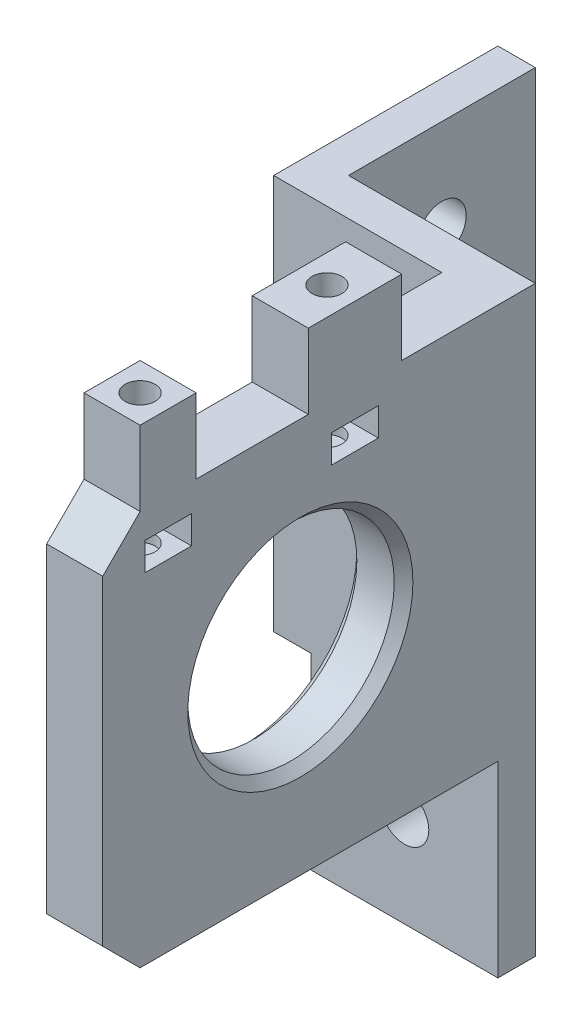
SolidWorks part; units mm, degrees
ref_plane "Přední rovina" through (0, 0, 0) normal (0, 0, 1) x (1, 0, 0)
ref_plane "Horní rovina" through (0, 0, 0) normal (0, 1, 0) x (1, 0, 0)
ref_plane "Pravá rovina" through (0, 0, 0) normal (1, 0, 0) x (0, 0, -1)
sketch "Skica2" plane through (0, 0, 0) normal (0, 0, 1) x (1, 0, 0)
  line L0 (-24.5243, -350) -> (-24.5243, 0) construction
  line L1 (-4.5243, -40) -> (-24.5243, -40)
  line L2 (-4.5243, -40) -> (-4.5243, -82.3)
  line L3 (-4.5243, -82.3) -> (-24.5243, -82.3)
  line L4 (-24.5243, -40) -> (-24.5243, -82.3)
  line L5 (-344.5243, -82.3) -> (-355.5243, -82.3) construction
extrude "Přidat vysunutím1" add sketch "Skica2" along normal blind 4
sketch "Skica3" plane through (-24.5243, 0, 0) normal (-1, 0, 0) x (0, 0, 1)
  line L0 (4, -82.3) -> (0, -82.3) construction
  line L1 (4, -40) -> (-20, -40)
  line L2 (4, -40) -> (4, -82.3)
  line L3 (4, -82.3) -> (-20, -82.3)
  line L4 (-20, -40) -> (-20, -82.3)
  line L5 (-20, -350) -> (-20, 0) construction
extrude "Přidat vysunutím2" add sketch "Skica3" along normal blind 4
sketch "Skica4" plane through (0, 0, 4) normal (0, 0, 1) x (1, 0, 0)
  line L0 (-28.5243, -82.3) -> (-4.5243, -82.3) construction
  line L1 (-10.5243, -40) -> (-4.5243, -40)
  line L2 (-10.5243, -40) -> (-10.5243, -82.3)
  line L3 (-10.5243, -82.3) -> (-4.5243, -82.3)
  line L4 (-4.5243, -40) -> (-4.5243, -82.3)
  line L5 (-4.5243, -82.3) -> (-4.5243, -40) construction
  dimension "D1" = 6
extrude "Přidat vysunutím3" add sketch "Skica4" along normal up to surface (42.3 mm away)
sketch "Skica5" plane through (-4.5243, 0, 0) normal (1, 0, 0) x (0, 0, -1)
  circle A0 centre (-25.15, -61.15) radius 11.05
  dimension "D1" = 22.1
extrude "Odebrat vysunutím1" cut sketch "Skica5" against normal blind 7
sketch "Skica7" plane through (-28.5243, 0, 0) normal (-1, 0, 0) x (0, 0, 1)
  line L0 (-20, -40) -> (-20, -82.3) construction
  line L1 (4, -40) -> (-20, -40) construction
  circle A0 centre (-10, -50) radius 2.6
  circle A1 centre (-10, -70) radius 2.6
  dimension "D3" = 5.2
  dimension "D1" = 10
  dimension "D2" = 10
  dimension "D4" = 2
extrude "Odebrat vysunutím3" cut sketch "Skica7" against normal blind 4
chamfer "Zkosení1" distance 1 angle 45 1 edges at (-10.5243, -50.1, 25.15)
sketch "Skica8" plane through (0, -82.3, 0) normal (0, -1, 0) x (1, 0, 0)
  line L0 (-28.5243, 4) -> (-10.5243, 4) construction
  line L1 (-4.5243, 0) -> (-24.5243, 0)
  line L2 (-4.5243, 0) -> (-4.5243, 4)
  line L3 (-4.5243, 4) -> (-24.5243, 4)
  line L4 (-24.5243, 0) -> (-24.5243, 4)
extrude "Přidat vysunutím4" add sketch "Skica8" along normal up to surface (20.0916 mm away)
sketch "Skica9" plane through (0, 0, 4) normal (0, 0, 1) x (1, 0, 0)
  line L0 (-24.5243, -102.3916) -> (-4.5243, -102.3916) construction
  line L1 (-4.5243, -102.3916) -> (-4.5243, -82.3) construction
  circle A0 centre (-14.5243, -92.3916) radius 2.6
  dimension "D3" = 5.2
  dimension "D1" = 10
  dimension "D2" = 10
extrude "Odebrat vysunutím4" cut sketch "Skica9" against normal blind 4
sketch "Skica10" plane through (-10.5243, 0, 0) normal (-1, 0, 0) x (0, 0, 1)
  line L0 (46.3, -44) -> (42.3, -40)
  line L1 (46.3, -40) -> (46.3, -82.3) construction
  line L2 (42.3, -40) -> (46.3, -44) construction
  line L3 (46.3, -40) -> (4, -40) construction
  line L4 (42.3, -40) -> (46.5659, -39.2593)
  line L5 (46.5659, -39.2593) -> (46.3, -44)
  line L6 (42.3, -82.3) -> (46.3, -78.3)
  line L7 (46.3, -82.3) -> (4, -82.3) construction
  line L8 (46.3, -78.3) -> (42.3, -82.3) construction
  line L9 (46.3, -78.3) -> (47.7456, -80.3)
  line L10 (47.7456, -80.3) -> (46.3, -85.4154)
  line L11 (46.3, -85.4154) -> (42.3, -82.3)
extrude "Odebrat vysunutím5" cut sketch "Skica10" against normal blind 80
sketch "Skica11" plane through (0, -40, 0) normal (0, 1, 0) x (1, 0, 0)
  line L0 (-4.5243, -42.3) -> (-4.5243, 0) construction
  line L1 (-10.5243, -42.3) -> (-4.5243, -42.3)
  line L2 (-10.5243, -42.3) -> (-10.5243, -36.3)
  line L3 (-10.5243, -36.3) -> (-4.5243, -36.3)
  line L4 (-4.5243, -42.3) -> (-4.5243, -36.3)
  line L5 (-10.5243, -42.3) -> (-10.5243, -4) construction
  line L6 (-4.5243, -24.3) -> (-10.5243, -24.3)
  line L7 (-4.5243, -24.3) -> (-4.5243, -14.3)
  line L8 (-4.5243, -14.3) -> (-10.5243, -14.3)
  line L9 (-10.5243, -24.3) -> (-10.5243, -14.3)
  line L10 (-384.5243, -36.3) -> (-4.5243, -36.3) construction
  line L11 (-384.5243, -24.3) -> (-4.5243, -24.3) construction
  dimension "D1" = 10
extrude "Přidat vysunutím5" add sketch "Skica11" along normal blind 8
sketch "Skica13" plane through (0, -32, 0) normal (0, 1, 0) x (1, 0, 0)
  line L0 (-4.5243, -42.3) -> (-4.5243, -36.3) construction
  line L1 (-4.5243, -24.3) -> (-4.5243, -14.3) construction
  circle A0 centre (-7.5243, -39.3) radius 1.6
  circle A1 centre (-7.5243, -19.3) radius 1.6
  point P7 (-4.5243, -19.3)
  point P8 (-4.5243, -39.3)
  dimension "D1" = 3.2
extrude "Odebrat vysunutím6" cut sketch "Skica13" against normal blind 15
sketch "Skica14" plane through (-4.5243, 0, 0) normal (1, 0, 0) x (0, 0, -1)
  line L0 (-39.3, -44.439) -> (-39.3, -32) construction
  line L1 (-41.8, -42.939) -> (-36.8, -42.939)
  line L2 (-41.8, -42.939) -> (-41.8, -45.939)
  line L3 (-41.8, -45.939) -> (-36.8, -45.939)
  line L4 (-36.8, -42.939) -> (-36.8, -45.939)
  line L5 (-41.8, -42.939) -> (-36.8, -45.939) construction
  line L6 (-41.8, -45.939) -> (-36.8, -42.939) construction
  line L7 (-42.3, -32) -> (-36.3, -32) construction
  line L8 (-19.3, -32) -> (-19.3, -44.439) construction
  line L9 (-24.3, -32) -> (-14.3, -32) construction
  line L11 (-16.8, -42.939) -> (-21.8, -42.939)
  line L12 (-16.8, -42.939) -> (-16.8, -45.939)
  line L13 (-16.8, -45.939) -> (-21.8, -45.939)
  line L14 (-21.8, -42.939) -> (-21.8, -45.939)
  line L15 (-16.8, -42.939) -> (-21.8, -45.939) construction
  line L16 (-16.8, -45.939) -> (-21.8, -42.939) construction
  point P0 (-39.3, -44.439)
  dimension "D1" = 5
  dimension "D2" = 3
extrude "Odebrat vysunutím7" cut sketch "Skica14" against normal blind 15
chamfer "Zkosení2" distance 1 angle 45 1 edges at (-4.5243, -61.15, 14.1)
